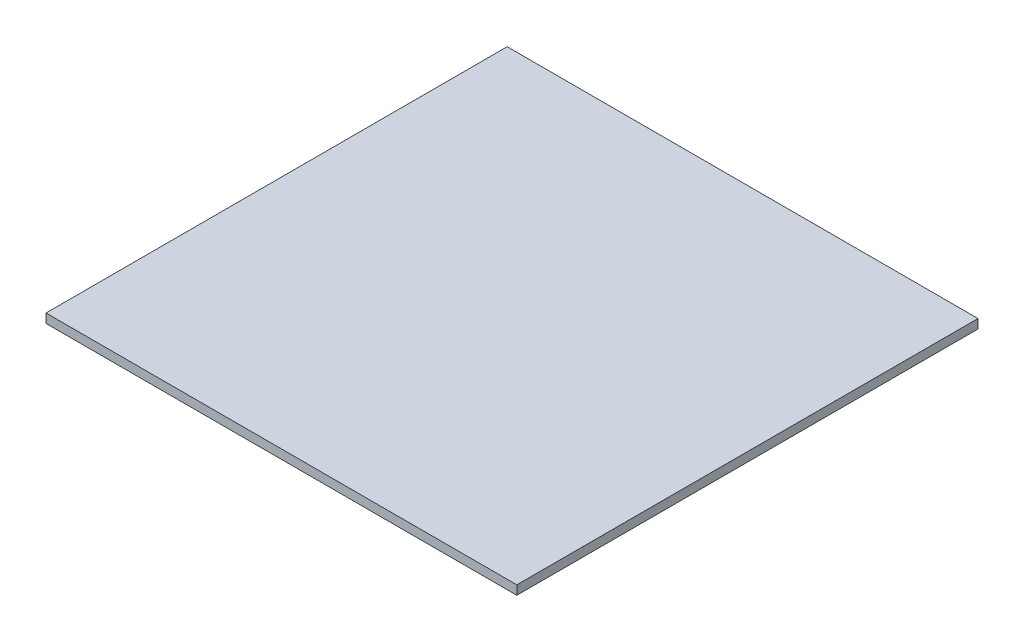
SolidWorks part; units mm, degrees
ref_plane "Front Plane" through (0, 0, 0) normal (0, 0, 1) x (1, 0, 0)
ref_plane "Top Plane" through (0, 0, 0) normal (0, 1, 0) x (1, 0, 0)
ref_plane "Right Plane" through (0, 0, 0) normal (1, 0, 0) x (0, 0, -1)
sketch "Sketch1" plane through (0, 0, 0) normal (0, 1, 0) x (1, 0, 0)
  line L1 (0, 0) -> (311.15, 0)
  line L2 (0, 0) -> (0, 304.8)
  line L3 (0, 304.8) -> (311.15, 304.8)
  line L4 (311.15, 0) -> (311.15, 304.8)
extrude "Boss-Extrude1" add sketch "Sketch1" along normal blind 6 contours L2 L1 L4 L3
sketch "Sketch2" plane through (0, 6, 0) normal (0, 1, 0) x (1, 0, 0)
  line L1 (0, 0) -> (311.15, 304.8)
  line L2 (0, 304.8) -> (311.15, 0)
  line L3 (156.8716, 153.1543) -> (156.3207, 153.7015)
  line L4 (156.3207, 153.7015) -> (155.5701, 153.9)
  line L5 (155.5701, 153.9) -> (154.8207, 153.6966)
  line L6 (154.8207, 153.6966) -> (154.2735, 153.1457)
  line L7 (154.2735, 153.1457) -> (154.075, 152.3951)
  line L8 (154.075, 152.3951) -> (154.2784, 151.6457)
  line L9 (154.2784, 151.6457) -> (154.8293, 151.0985)
  line L10 (154.8293, 151.0985) -> (155.5799, 150.9)
  line L11 (155.5799, 150.9) -> (156.3293, 151.1034)
  line L12 (156.3293, 151.1034) -> (156.8765, 151.6543)
  line L13 (156.8765, 151.6543) -> (157.075, 152.4049)
  line L14 (157.075, 152.4049) -> (156.8716, 153.1543)
  circle A1 centre (155.575, 152.4) radius 25.4
  circle A3 centre (155.575, 152.4) radius 1.4489 construction
